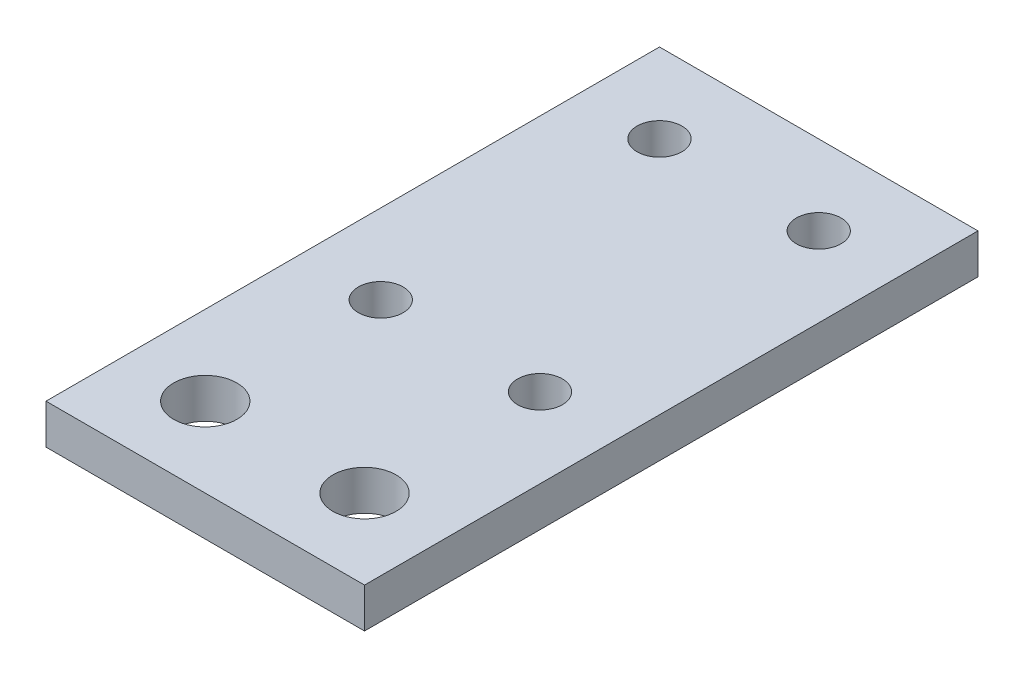
SolidWorks part; units mm, degrees
material "Plain Carbon Steel"
ref_plane "Front Plane" through (0, 0, 0) normal (0, 0, 1) x (1, 0, 0)
ref_plane "Top Plane" through (0, 0, 0) normal (0, 1, 0) x (1, 0, 0)
ref_plane "Right Plane" through (0, 0, 0) normal (1, 0, 0) x (0, 0, -1)
sketch "Sketch1" plane through (0, 0, 0) normal (0, 0, 1) x (1, 0, 0)
  line L1 (-25.4, -3.175) -> (25.4, -3.175)
  line L2 (-25.4, -3.175) -> (-25.4, 3.175)
  line L3 (-25.4, 3.175) -> (25.4, 3.175)
  line L4 (25.4, -3.175) -> (25.4, 3.175)
  line L5 (-25.4, -3.175) -> (25.4, 3.175) construction
  line L6 (-25.4, 3.175) -> (25.4, -3.175) construction
  point P0 (0, 0)
  dimension "D1" = 50.8
  dimension "D2" = 6.35
extrude "Extrude1" add sketch "Sketch1" along normal blind 97.8408
sketch "Sketch3" plane through (0, 3.175, 0) normal (0, 1, 0) x (1, 0, 0)
  line L0 (25.4, -85.1408) -> (12.7, -85.1408) construction
  line L1 (25.4, -97.8408) -> (25.4, 0) construction
  line L3 (12.7, 0) -> (12.7, -12.7) construction
  line L4 (25.4, 0) -> (-25.4, 0) construction
  line L5 (12.7, -12.7) -> (12.7, -57.15) construction
  dimension "D1" = 12.7
  dimension "D2" = 12.7
  dimension "D3" = 12.7
  dimension "D4" = 12.7
  dimension "D5" = 44.45
hole_wizard "3/8 Clearance Hole1" positions "3DSketch1" profile "Sketch4" hole size "3/8" standard "Ansi Inch"
sketch3d "3DSketch1"
  point P0 (12.7, 3.175, 85.1408)
sketch "Sketch4" plane through (12.7, 3.175, 85.1408) normal (1, 0, 0) x (0, 0, 1)
  line L0 (0, 0) -> (0, 19.0315)
  line L1 (0, 19.0315) -> (5.0419, 16.002)
  line L2 (5.0419, 16.002) -> (5.0419, 0)
  line L5 (5.0419, 0) -> (0, 0)
  line L10 (0, 19.0315) -> (-5.0419, 16.002) construction
  line L11 (0, -6.35) -> (0, 107.95) construction
  dimension "Hole Dia." = 10.0838
  dimension "Hole Depth" = 16.002
  dimension "Drill Angle" = 118
hole_wizard "1/4 Clearance Hole1" positions "3DSketch2" profile "Sketch5" hole size "1/4" standard "Ansi Inch"
sketch3d "3DSketch2"
  point P0 (12.7, 3.175, 57.15)
  point P5 (12.7, 3.175, 12.7)
sketch "Sketch5" plane through (12.7, 3.175, 57.15) normal (1, 0, 0) x (0, 0, 1)
  line L0 (0, 0) -> (0, 18.1478)
  line L1 (0, 18.1478) -> (3.5712, 16.002)
  line L2 (3.5712, 16.002) -> (3.5712, 0)
  line L5 (3.5712, 0) -> (0, 0)
  line L10 (0, 18.1478) -> (-3.5712, 16.002) construction
  line L11 (0, -6.35) -> (0, 107.95) construction
  dimension "Hole Dia." = 7.1425
  dimension "Hole Depth" = 16.002
  dimension "Drill Angle" = 118
mirror "Mirror1" about plane through (0, 0, 0) normal (1, 0, 0) of "3/8 Clearance Hole1", "1/4 Clearance Hole1"
sketch "Sketch6" plane through (0, 3.175, 0) normal (0, 1, 0) x (1, 0, 0)
  line L0 (-25.4, -97.8408) -> (-25.4, 0) construction
  line L1 (-25.4, -95.676) -> (25.4, -95.676)
  line L2 (-25.4, -95.676) -> (-25.4, -83.0145)
  line L3 (-25.4, -83.0145) -> (25.4, -83.0145)
  line L4 (25.4, -95.676) -> (25.4, -83.0145)
  line L5 (25.4, -97.8408) -> (25.4, 0) construction
extrude "Extrude2" [suppressed] add sketch "Sketch6" along normal blind 5.08
